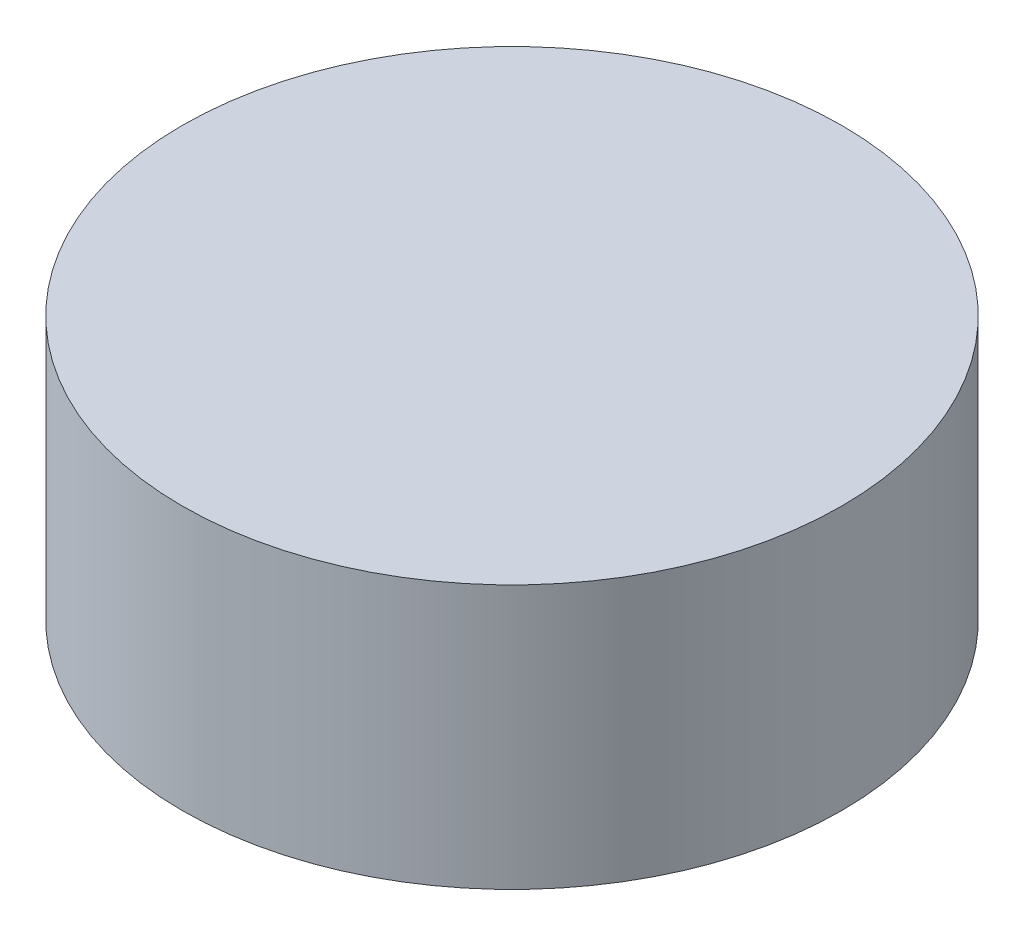
SolidWorks part; units mm, degrees
ref_plane "Front" through (0, 0, 0) normal (0, 0, 1) x (1, 0, 0)
ref_plane "Top" through (0, 0, 0) normal (0, 1, 0) x (1, 0, 0)
ref_plane "Right" through (0, 0, 0) normal (1, 0, 0) x (0, 0, -1)
sketch "스케치1" plane through (0, 0, 0) normal (0, 1, 0) x (1, 0, 0)
  circle A0 centre (0, 0) radius 2.5
extrude "보스-돌출1" add sketch "스케치1" along normal blind 2
